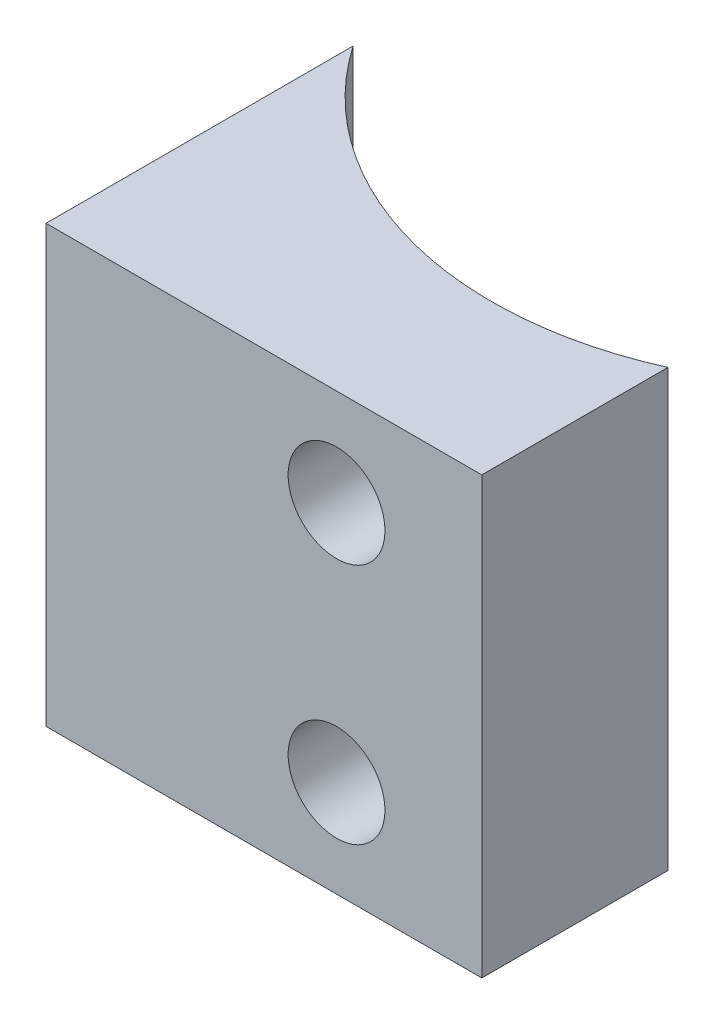
SolidWorks part; units mm, degrees
ref_plane "Front Plane" through (0, 0, 0) normal (0, 0, 1) x (1, 0, 0)
ref_plane "Top Plane" through (0, 0, 0) normal (0, 1, 0) x (1, 0, 0)
ref_plane "Right Plane" through (0, 0, 0) normal (1, 0, 0) x (0, 0, -1)
sketch "Sketch1" plane through (0, 0, 0) normal (0, 1, 0) x (1, 0, 0)
  line L1 (-30, -20) -> (15, -20)
  line L2 (-30, -20) -> (-30, -52.5)
  line L3 (-30, -52.5) -> (15, -52.5)
  line L4 (15, -20) -> (15, -52.5)
  circle A0 centre (0, 0) radius 36.5
  dimension "D1" = 73
  dimension "D2" = 52.5
  dimension "D3" = 45
  dimension "D4" = 15
  dimension "D5" = 32.5
extrude "Boss-Extrude1" add sketch "Sketch1" along normal blind 15 and the other way blind 30 contours A0 L1 L2 L3 L4
sketch "Sketch2" plane through (0, 0, 52.5) normal (0, 0, 1) x (1, 0, 0)
  line L0 (-30, 15) -> (15, 15) construction
  circle A0 centre (0, -20) radius 5
  circle A1 centre (0, 5) radius 5
  point P6 (0, 0)
  dimension "D1" = 10
  dimension "D2" = 10
  dimension "D3" = 25
  dimension "D4" = 10
extrude "Cut-Extrude1" cut sketch "Sketch2" against normal through all
